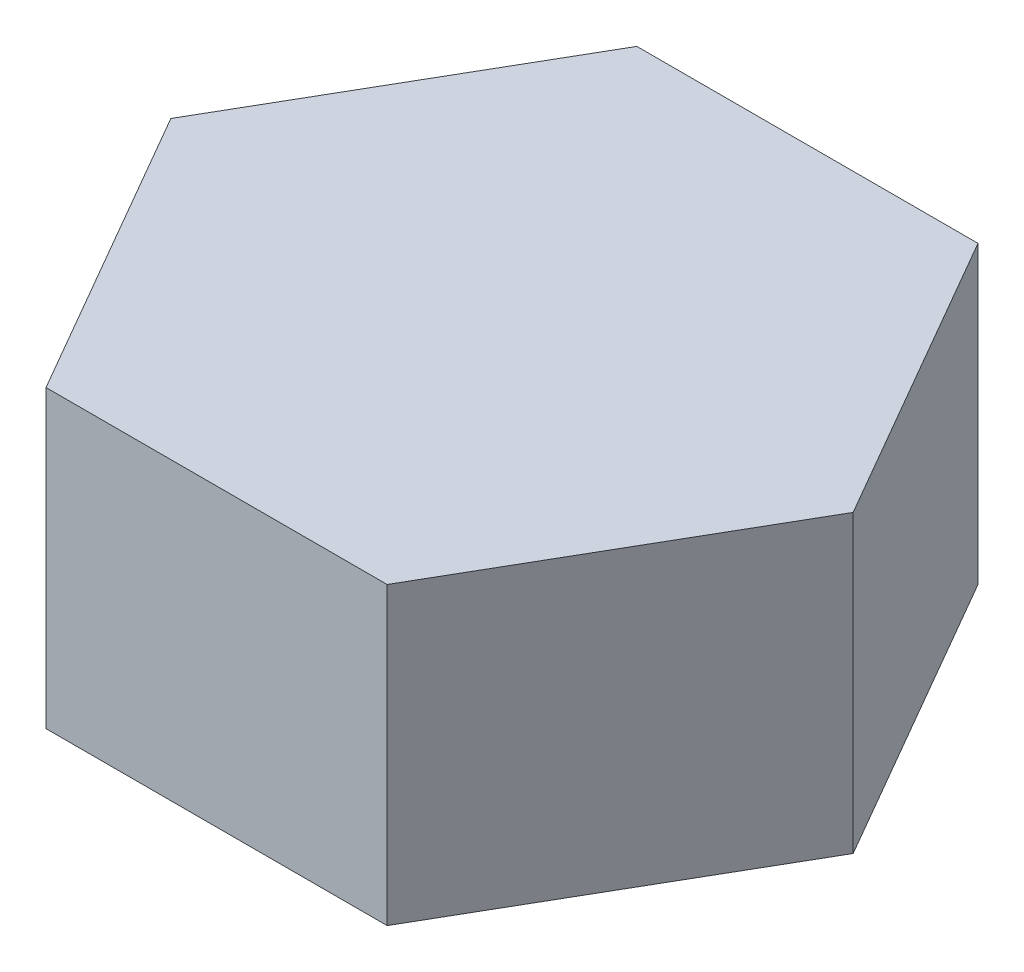
SolidWorks part; units mm, degrees
material "보통 탄소강"
ref_plane "Front" through (0, 0, 0) normal (0, 0, 1) x (1, 0, 0)
ref_plane "Top" through (0, 0, 0) normal (0, 1, 0) x (1, 0, 0)
ref_plane "Right" through (0, 0, 0) normal (1, 0, 0) x (0, 0, -1)
sketch "Sketch1" plane through (0, 0, 0) normal (0, 1, 0) x (1, 0, 0)
  line L1 (-86.6025, 150) -> (-173.2051, 0)
  line L2 (-173.2051, 0) -> (-86.6025, -150)
  line L3 (-86.6025, -150) -> (86.6025, -150)
  line L4 (86.6025, -150) -> (173.2051, 0)
  line L5 (173.2051, 0) -> (86.6025, 150)
  line L6 (86.6025, 150) -> (-86.6025, 150)
  circle A0 centre (0, 0) radius 150 construction
  dimension "D1" = 300
extrude "Extrude1" add sketch "Sketch1" along normal blind 150
equation "\"D\" = 300mm"
equation "\"H\"= 150mm"
equation "\"D1@Sketch1\"= \"D\""
equation "\"D1@Extrude1\"= \"H\""
